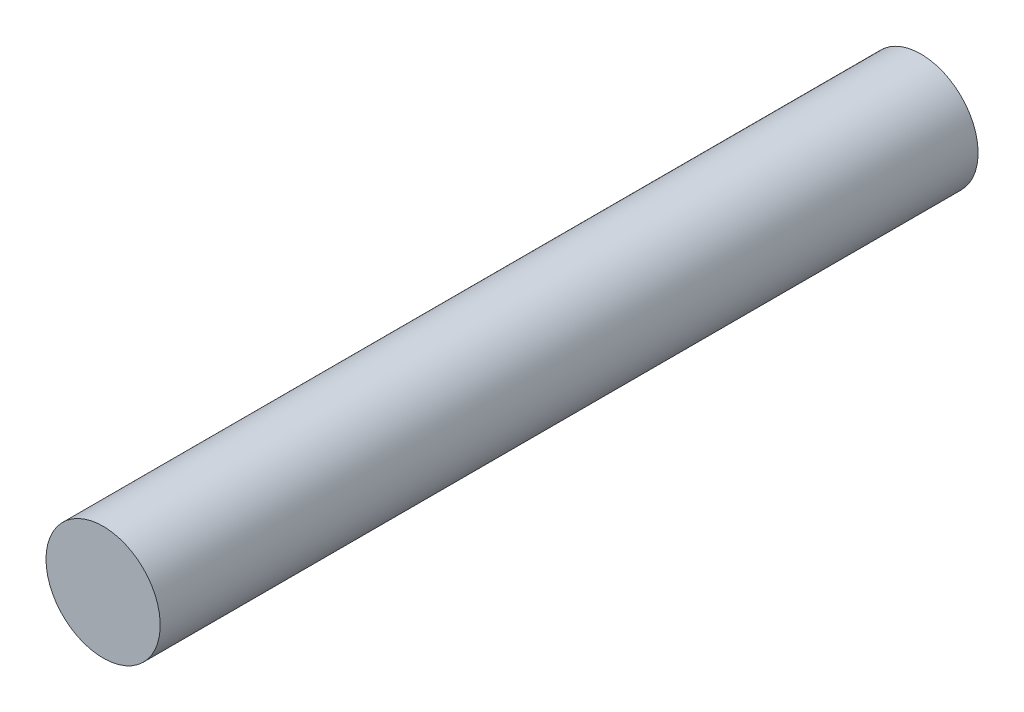
SolidWorks part; units mm, degrees
ref_plane "Front Plane" through (0, 0, 0) normal (0, 0, 1) x (1, 0, 0)
ref_plane "Top Plane" through (0, 0, 0) normal (0, 1, 0) x (1, 0, 0)
ref_plane "Right Plane" through (0, 0, 0) normal (1, 0, 0) x (0, 0, -1)
sketch "Sketch1" plane through (0, 0, 0) normal (0, 0, 1) x (1, 0, 0)
  circle A0 centre (0, 0) radius 2.5
  dimension "D1" = 5
extrude "Boss-Extrude1" add sketch "Sketch1" along normal blind 35.8
